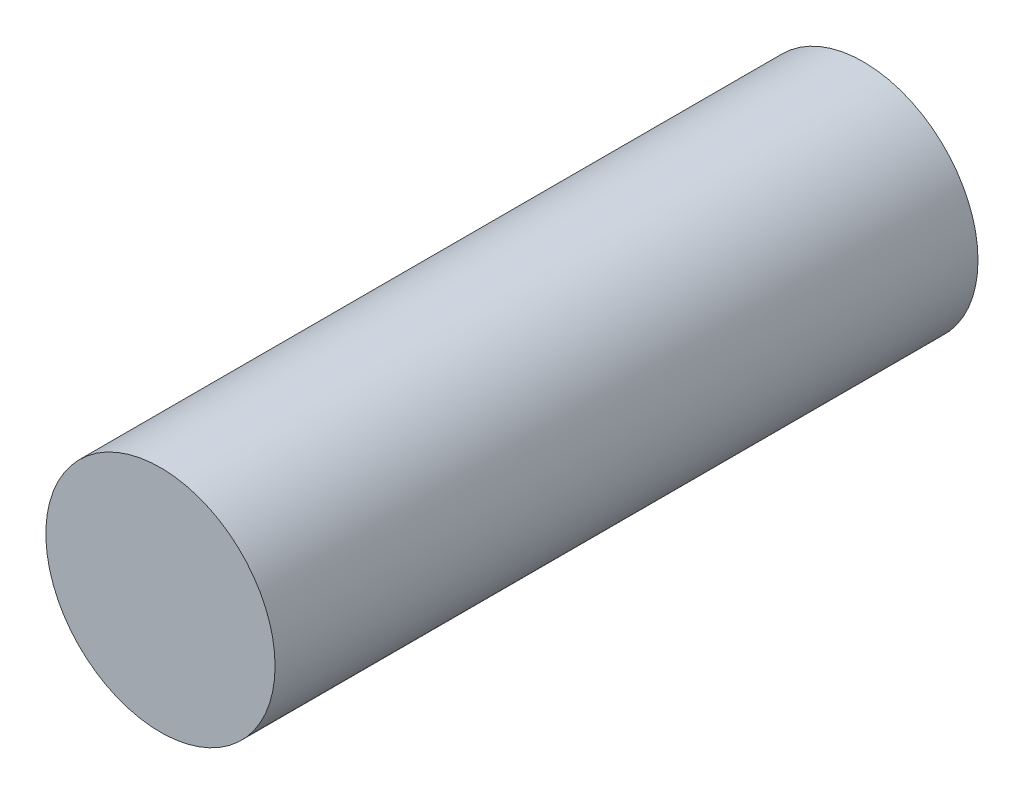
SolidWorks part; units mm, degrees
ref_plane "Alzado" through (0, 0, 0) normal (0, 0, 1) x (1, 0, 0)
ref_plane "Planta" through (0, 0, 0) normal (0, 1, 0) x (1, 0, 0)
ref_plane "Vista lateral" through (0, 0, 0) normal (1, 0, 0) x (0, 0, -1)
sketch "Croquis1" plane through (0, 0, 0) normal (0, 0, 1) x (1, 0, 0)
  circle A0 centre (0, 0) radius 6
  dimension "D1" = 12
extrude "Saliente-Extruir1" add sketch "Croquis1" along normal blind 36.8
